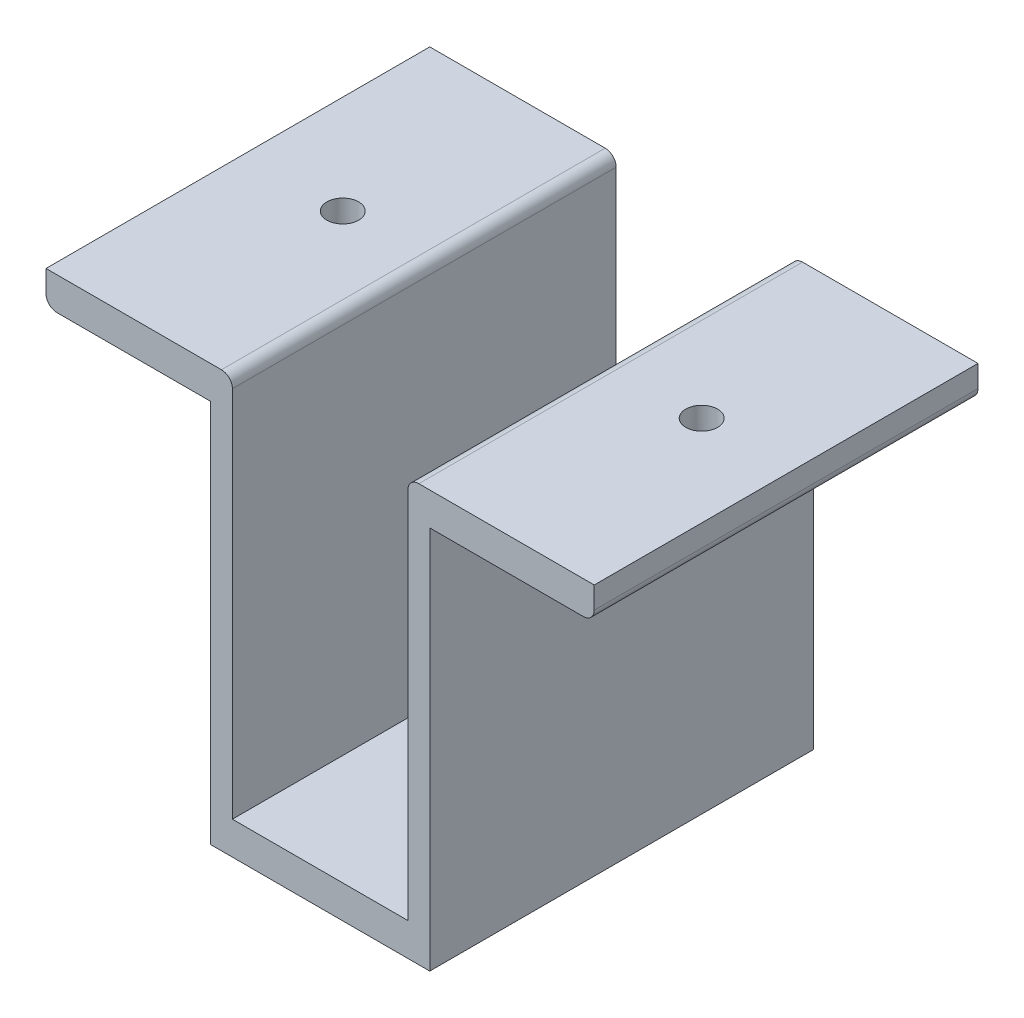
SolidWorks part; units mm, degrees
material "ABS"
ref_plane "Front Plane" through (0, 0, 0) normal (0, 0, 1) x (1, 0, 0)
ref_plane "Top Plane" through (0, 0, 0) normal (0, 1, 0) x (1, 0, 0)
ref_plane "Right Plane" through (0, 0, 0) normal (1, 0, 0) x (0, 0, -1)
sketch "Sketch2" plane through (0, 0, 0) normal (0, 1, 0) x (1, 0, 0)
  line L1 (0, 19.8875) -> (20, 19.8875)
  line L2 (0, 19.8875) -> (0, -15.1125)
  line L3 (0, -15.1125) -> (20, -15.1125)
  line L4 (20, 19.8875) -> (20, -15.1125)
  dimension "D1" = 20
  dimension "D2" = 35
extrude "Boss-Extrude1" add sketch "Sketch2" along normal blind 3
sketch "Sketch3" plane through (0, 3, 0) normal (0, 1, 0) x (1, 0, 0)
  line L1 (0, 19.8875) -> (2, 19.8875)
  line L2 (0, 19.8875) -> (0, -15.1125)
  line L3 (0, -15.1125) -> (2, -15.1125)
  line L4 (2, 19.8875) -> (2, -15.1125)
  line L9 (20, 19.8875) -> (17.9994, 19.8875)
  line L10 (20, 19.8875) -> (20, -15.1125)
  line L11 (20, -15.1125) -> (17.9994, -15.1125)
  line L12 (17.9994, 19.8875) -> (17.9994, -15.1125)
  dimension "D1" = 2
  dimension "D2" = 15.9994
extrude "Boss-Extrude2" add sketch "Sketch3" along normal blind 35
sketch "Sketch4" plane through (20, 0, 0) normal (1, 0, 0) x (0, 0, -1)
  line L0 (-15.1125, 38) -> (19.8875, 38) construction
  line L1 (-15.1125, 38) -> (19.8875, 38)
  line L2 (-15.1125, 38) -> (-15.1125, 35.0081)
  line L3 (-15.1125, 35.0081) -> (19.8875, 35.0081)
  line L4 (19.8875, 38) -> (19.8875, 35.0081)
  dimension "D1" = 0
extrude "Boss-Extrude3" add sketch "Sketch4" along normal blind 15
sketch "Sketch5" plane through (0, 0, 0) normal (-1, 0, 0) x (0, 0, 1)
  line L0 (-19.8875, 38) -> (15.1125, 38) construction
  line L1 (-19.8875, 38) -> (15.1125, 38)
  line L2 (-19.8875, 38) -> (-19.8875, 35.0081)
  line L3 (-19.8875, 35.0081) -> (15.1125, 35.0081)
  line L4 (15.1125, 38) -> (15.1125, 35.0081)
  dimension "D1" = 0
extrude "Boss-Extrude4" add sketch "Sketch5" along normal blind 15
sketch "Sketch6" plane through (0, 3, 0) normal (0, 1, 0) x (1, 0, 0)
  line L5 (17.9994, 19.8875) -> (2, 19.8875)
  line L6 (17.9994, 19.8875) -> (17.9994, 17.8952)
  line L7 (17.9994, 17.8952) -> (2, 17.8952)
  line L8 (2, 19.8875) -> (2, 17.8952)
extrude "Boss-Extrude5" add sketch "Sketch6" along normal blind 5
sketch "Sketch8" plane through (0, 38, 0) normal (0, 1, 0) x (1, 0, 0)
  line L1 (-15, -15.1125) -> (-6.0021, -15.1125) construction
  line L2 (-15, -15.1125) -> (-15, 2.9555) construction
  line L3 (-15, 2.9555) -> (-6.0021, 2.9555) construction
  line L4 (-6.0021, -15.1125) -> (-6.0021, 2.9555) construction
  line L5 (35, -15.1125) -> (26.7304, -15.1125) construction
  line L6 (35, -15.1125) -> (35, 2.9555) construction
  line L7 (35, 2.9555) -> (26.7304, 2.9555) construction
  line L8 (26.7304, -15.1125) -> (26.7304, 2.9555) construction
  circle A0 centre (-6.0021, 2.9555) radius 1.45
  circle A1 centre (26.7304, 2.9555) radius 1.45
  dimension "D1" = 2.9
  dimension "D2" = 2.9
extrude "Cut-Extrude1" cut sketch "Sketch8" against normal through all
fillet "Fillet1" radius 1 4 edges at (-15, 35.0081, -2.3875) (35, 35.0081, -2.3875) (17.9994, 38, -2.3875) (2, 38, -2.3875)
fillet "Fillet3" radius 1 1 edges at (9.9997, 8, -19.8875)
